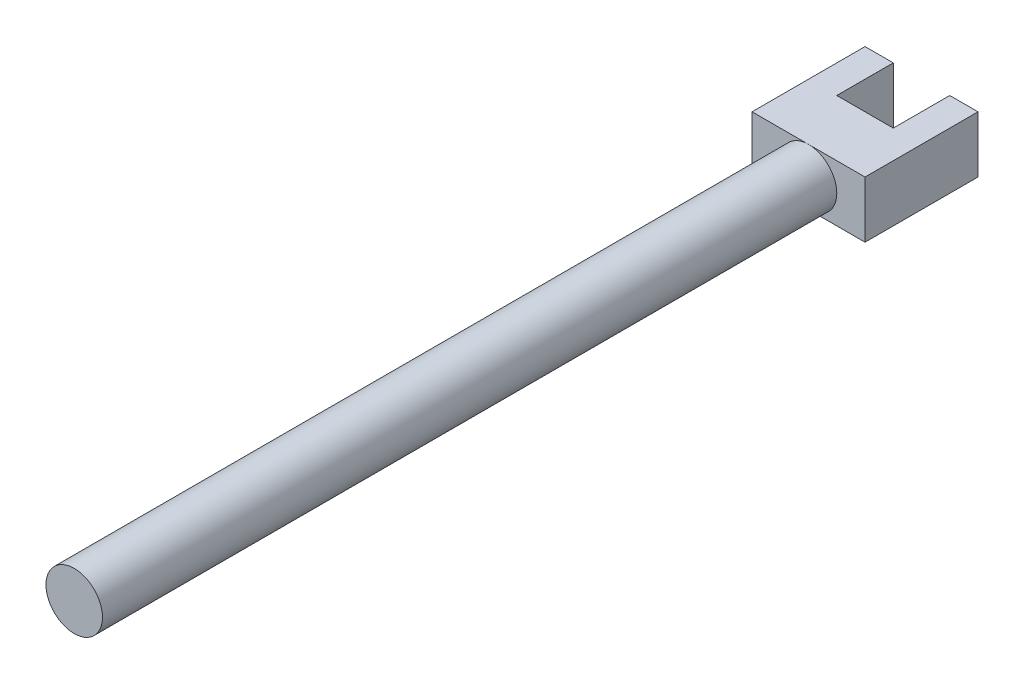
SolidWorks part; units mm, degrees
ref_plane "Front Plane" through (0, 0, 0) normal (0, 0, 1) x (1, 0, 0)
ref_plane "Top Plane" through (0, 0, 0) normal (0, 1, 0) x (1, 0, 0)
ref_plane "Right Plane" through (0, 0, 0) normal (1, 0, 0) x (0, 0, -1)
sketch "Sketch1" plane through (0, 0, 0) normal (0, 0, 1) x (1, 0, 0)
  circle A0 centre (0, 0) radius 5
extrude "Boss-Extrude1" add sketch "Sketch1" along normal blind 130
sketch "Sketch2" plane through (0, 0, 0) normal (0, 0, -1) x (-1, 0, 0)
  line L1 (-10, -5) -> (10, -5)
  line L2 (-10, -5) -> (-10, 5)
  line L3 (-10, 5) -> (10, 5)
  line L4 (10, -5) -> (10, 5)
  line L5 (-10, -5) -> (10, 5) construction
  line L6 (-10, 5) -> (10, -5) construction
  point P0 (0, 0)
  dimension "D1" = 20
  dimension "D2" = 10
extrude "Boss-Extrude2" add sketch "Sketch2" along normal blind 10
sketch "Sketch3" plane through (0, 0, -10) normal (0, 0, -1) x (-1, 0, 0)
  line L0 (-10, -5) -> (10, -5) construction
  line L1 (-10, 5) -> (-5, 5)
  line L2 (-10, 5) -> (-10, -5)
  line L3 (-10, -5) -> (-5, -5)
  line L4 (-5, 5) -> (-5, -5)
  dimension "D1" = 5
extrude "Boss-Extrude3" add sketch "Sketch3" along normal blind 10
sketch "Sketch4" plane through (0, 0, -10) normal (0, 0, -1) x (-1, 0, 0)
  line L0 (-5, -5) -> (10, -5) construction
  line L1 (10, 5) -> (5, 5)
  line L2 (10, 5) -> (10, -5)
  line L3 (10, -5) -> (5, -5)
  line L4 (5, 5) -> (5, -5)
  dimension "D1" = 5
extrude "Boss-Extrude4" add sketch "Sketch4" along normal blind 10
sketch "Sketch5" plane through (0, 0, -10) normal (0, 0, -1) x (-1, 0, 0)
  point P0 (0, 0)
